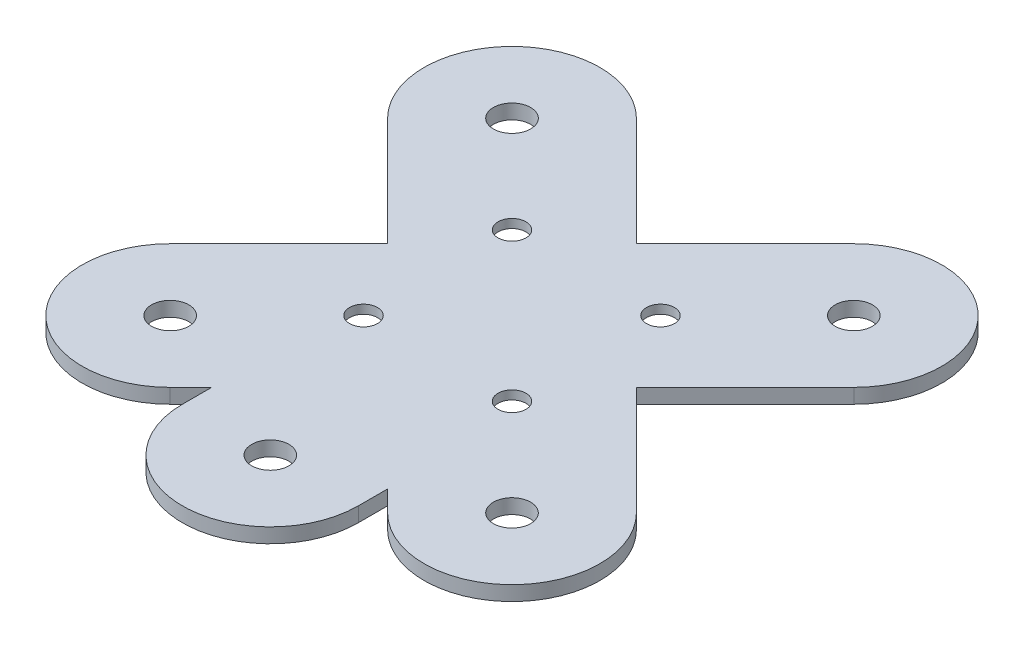
SolidWorks part; units mm, degrees
ref_plane "Front" through (0, 0, 0) normal (0, 0, 1) x (1, 0, 0)
ref_plane "Top" through (0, 0, 0) normal (0, 1, 0) x (1, 0, 0)
ref_plane "Right" through (0, 0, 0) normal (1, 0, 0) x (0, 0, -1)
sketch "Esquisse2" plane through (0, 0, 0) normal (0, 1, 0) x (1, 0, 0)
  line L0 (-30, 30) -> (30, -30) construction
  line L1 (30, 30) -> (30, -30) construction
  line L2 (30, -30) -> (-30, -30) construction
  line L3 (-30, -30) -> (-30, 30) construction
  line L4 (-30, 30) -> (30, 30) construction
  line L5 (30, 30) -> (-30, -30) construction
  line L6 (-1.7157, 1.7157) -> (-58.2843, 58.2843) construction
  line L7 (-22.9289, -19.4975) -> (-79.4975, 37.0711)
  line L8 (19.4975, 22.9289) -> (-37.0711, 79.4975)
  line L11 (5, 11.5685) -> (5, 91.5685) construction
  line L15 (1.7157, 1.7157) -> (58.2843, 58.2843) construction
  line L16 (-19.4975, 22.9289) -> (37.0711, 79.4975)
  line L17 (21.5685, -5) -> (101.5685, -5) construction
  line L20 (22.9289, -19.4975) -> (79.4975, 37.0711)
  line L28 (1.7157, -1.7157) -> (58.2843, -58.2843) construction
  line L29 (-11.5685, -5) -> (-91.5685, -5) construction
  line L30 (22.9289, 19.4975) -> (79.4975, -37.0711)
  line L31 (-19.4975, -22.9289) -> (37.0711, -79.4975)
  line L32 (0, -2.4264) -> (0, -82.4264) construction
  line L33 (30, -2.4264) -> (30, -82.4264)
  line L34 (-30, -2.4264) -> (-30, -82.4264)
  line L35 (-1.7157, -1.7157) -> (-58.2843, -58.2843) construction
  line L36 (19.4975, -22.9289) -> (-37.0711, -79.4975)
  line L37 (-22.9289, 19.4975) -> (-79.4975, -37.0711)
  line L59 (0, 2.4264) -> (0, 82.4264) construction
  line L60 (-30, 2.4264) -> (-30, 82.4264)
  line L61 (30, 2.4264) -> (30, 82.4264)
  line L62 (2.4264, 0) -> (82.4264, 0) construction
  line L63 (2.4264, 30) -> (82.4264, 30)
  line L64 (2.4264, -30) -> (82.4264, -30)
  line L65 (-2.4264, 0) -> (-82.4264, 0) construction
  line L66 (-2.4264, -30) -> (-82.4264, -30)
  line L67 (-2.4264, 30) -> (-82.4264, 30)
  line L68 (0, 2.4264) -> (0, 82.4264) construction
  line L69 (-30, 2.4264) -> (-30, 82.4264)
  line L70 (30, 2.4264) -> (30, 82.4264)
  line L71 (2.4264, 0) -> (82.4264, 0) construction
  line L72 (2.4264, 30) -> (82.4264, 30)
  line L73 (2.4264, -30) -> (82.4264, -30)
  line L74 (-2.4264, 0) -> (-82.4264, 0) construction
  line L75 (-2.4264, -30) -> (-82.4264, -30)
  line L76 (-2.4264, 30) -> (-82.4264, 30)
  arc A0 (-22.9289, -19.4975) -> (19.4975, 22.9289) centre (-1.7157, 1.7157) ccw
  arc A1 (-37.0711, 79.4975) -> (-79.4975, 37.0711) centre (-58.2843, 58.2843) ccw
  arc A6 (-19.4975, 22.9289) -> (22.9289, -19.4975) centre (1.7157, 1.7157) ccw
  arc A7 (79.4975, 37.0711) -> (37.0711, 79.4975) centre (58.2843, 58.2843) ccw
  arc A16 (22.9289, 19.4975) -> (-19.4975, -22.9289) centre (1.7157, -1.7157) ccw
  arc A17 (37.0711, -79.4975) -> (79.4975, -37.0711) centre (58.2843, -58.2843) ccw
  arc A18 (30, -2.4264) -> (-30, -2.4264) centre (0, -2.4264) ccw
  arc A19 (-30, -82.4264) -> (30, -82.4264) centre (0, -82.4264) ccw
  arc A20 (19.4975, -22.9289) -> (-22.9289, 19.4975) centre (-1.7157, -1.7157) ccw
  arc A21 (-79.4975, -37.0711) -> (-37.0711, -79.4975) centre (-58.2843, -58.2843) ccw
  arc A42 (-30, 2.4264) -> (30, 2.4264) centre (0, 2.4264) ccw
  arc A43 (30, 82.4264) -> (-30, 82.4264) centre (0, 82.4264) ccw
  arc A44 (2.4264, 30) -> (2.4264, -30) centre (2.4264, 0) ccw
  arc A45 (82.4264, -30) -> (82.4264, 30) centre (82.4264, 0) ccw
  arc A46 (-2.4264, -30) -> (-2.4264, 30) centre (-2.4264, 0) ccw
  arc A47 (-82.4264, 30) -> (-82.4264, -30) centre (-82.4264, 0) ccw
  point P0 (0, 0)
  point P9 (-30, 30)
  point P19 (5, 51.5685)
  point P22 (0, 49.4975)
  point P29 (30, 30)
  point P33 (61.5685, -5)
  point P39 (49.4975, 0)
  point P46 (30, -30)
  point P53 (0, -42.4264)
  point P61 (-51.5685, -5)
  point P63 (-30, -30)
  point P66 (5, -5)
  point P71 (-49.4975, 0)
  point P76 (0, 0)
  point P109 (0, 49.4975)
  point P116 (49.4975, 0)
  point P123 (-49.4975, 0)
  point P130 (0, 42.4264)
  point P137 (42.4264, 0)
  point P144 (-42.4264, 0)
  point P151 (0, 42.4264)
  point P158 (42.4264, 0)
  point P165 (-42.4264, 0)
  point P172 (0, 42.4264)
  point P179 (42.4264, 0)
  point P186 (-42.4264, 0)
  dimension "D4" = 30
  dimension "D1" = 60
  dimension "D2" = 60
  dimension "D3" = 80
  dimension "D5" = 8
extrude "Boss.-Extru.1" add sketch "Esquisse2" along normal blind 5
sketch "Esquisse4" plane through (0, 0, 0) normal (0, -1, 0) x (-1, 0, 0)
  line L0 (0, 0) -> (-79.4975, -79.4975) construction
  line L1 (-25.317, -46.5302) -> (-7.6393, -28.8525)
  line L2 (-7.6393, -28.8525) -> (-28.8525, -7.6393)
  line L3 (-28.8525, -7.6393) -> (-46.5302, -25.317)
  line L4 (-42.4264, 0) -> (-79.4975, -37.0711) construction
  line L5 (-46.5302, 25.317) -> (-28.8525, 7.6393)
  line L6 (-7.6393, 28.8525) -> (-25.317, 46.5302)
  line L7 (-28.8525, 7.6393) -> (-7.6393, 28.8525)
  line L8 (25.317, 46.5302) -> (7.6393, 28.8525)
  line L9 (28.8525, 7.6393) -> (46.5302, 25.317)
  line L10 (7.6393, 28.8525) -> (28.8525, 7.6393)
  line L11 (46.5302, -25.317) -> (28.8525, -7.6393)
  line L12 (7.6393, -28.8525) -> (25.317, -46.5302)
  line L13 (28.8525, -7.6393) -> (7.6393, -28.8525)
  arc A0 (-79.4975, -37.0711) -> (-37.0711, -79.4975) centre (-58.2843, -58.2843) ccw construction
  arc A1 (-25.317, -46.5302) -> (-46.5302, -25.317) centre (-58.2843, -58.2843) ccw
  arc A2 (-46.5302, 25.317) -> (-25.317, 46.5302) centre (-58.2843, 58.2843) ccw
  arc A3 (25.317, 46.5302) -> (46.5302, 25.317) centre (58.2843, 58.2843) ccw
  arc A4 (46.5302, -25.317) -> (25.317, -46.5302) centre (58.2843, -58.2843) ccw
  point P36 (0, 0)
  dimension "D5" = 35
  dimension "D1" = 25
  dimension "D2" = 25
  dimension "D3" = 15
  dimension "D4" = 30
extrude "Enlèv. mat.-Extru.1" cut sketch "Esquisse4" against normal blind 2 contours L0 L2 L3 A1 | L2 L0 A1 L1 | A2 L5 L7 L6 | A3 L8 L10 L9 | A4 L11 L13 L12
sketch "Esquisse5" plane through (0, 2, 0) normal (0, -1, 0) x (-1, 0, 0)
  line L0 (0, 0) -> (-58.2843, -58.2843) construction
  line L1 (-58.2843, -58.2843) -> (0, 0) construction
  line L2 (-7.6393, -28.8525) -> (-28.8525, -7.6393) construction
  circle A0 centre (-25.317, -25.317) radius 4.7625
  circle A1 centre (-25.317, 25.317) radius 4.7625
  circle A2 centre (25.317, 25.317) radius 4.7625
  circle A3 centre (25.317, -25.317) radius 4.7625
  point P17 (0, 0)
  dimension "D1" = 9.525
  dimension "D2" = 10
extrude "Enlèv. mat.-Extru.2" cut sketch "Esquisse5" against normal through all
sketch "Esquisse7" plane through (0, 0, 0) normal (0, -1, 0) x (-1, 0, 0)
  circle A0 centre (0, -82.4264) radius 6.35
  circle A1 centre (-58.2843, -58.2843) radius 6.35
  circle A2 centre (-82.4264, 0) radius 6.35 [skipped]
  circle A3 centre (-58.2843, 58.2843) radius 6.35
  circle A4 centre (0, 82.4264) radius 6.35 [skipped]
  circle A5 centre (58.2843, 58.2843) radius 6.35
  circle A6 centre (82.4264, 0) radius 6.35 [skipped]
  circle A7 centre (58.2843, -58.2843) radius 6.35
  point P20 (0, 0)
  dimension "D1" = 12.7
extrude "Enlèv. mat.-Extru.3" cut sketch "Esquisse7" against normal through all
